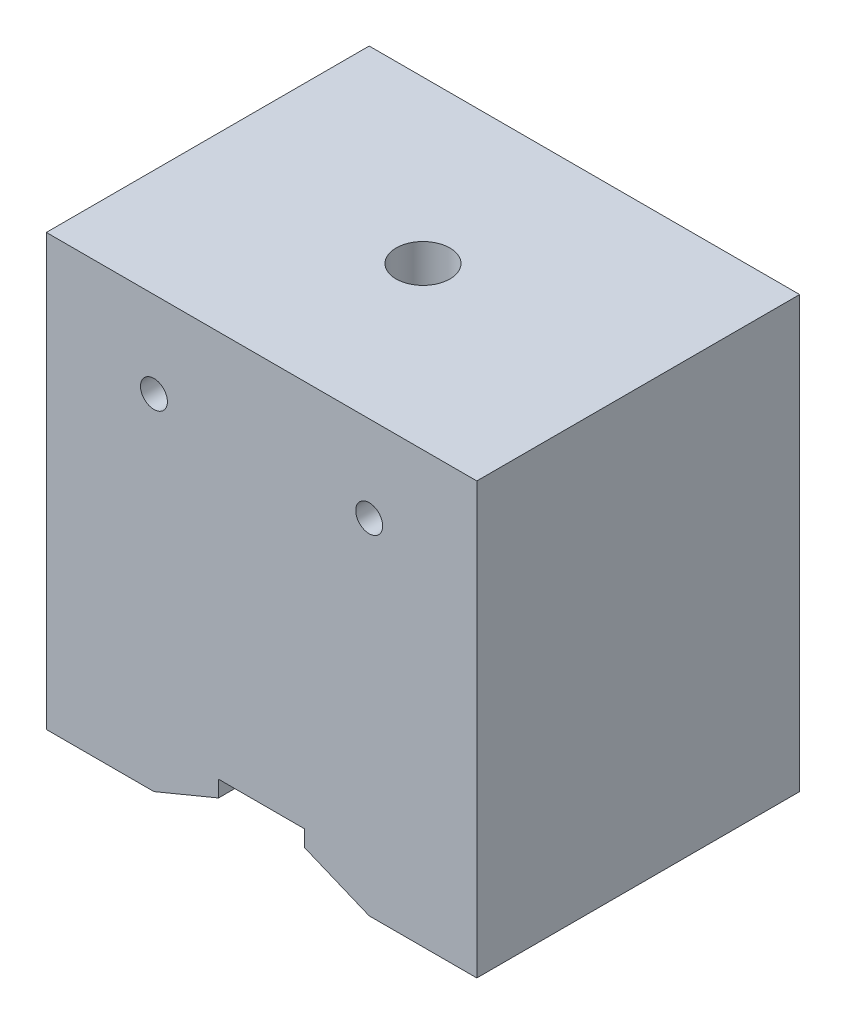
SolidWorks part; units mm, degrees
ref_plane "前视基准面" through (0, 0, 0) normal (0, 0, 1) x (1, 0, 0)
ref_plane "上视基准面" through (0, 0, 0) normal (0, 1, 0) x (1, 0, 0)
ref_plane "右视基准面" through (0, 0, 0) normal (1, 0, 0) x (0, 0, -1)
sketch "草图1" plane through (0, 0, 0) normal (0, 0, 1) x (1, 0, 0)
  line L1 (0, 0) -> (40, 0)
  line L2 (0, 0) -> (0, 40)
  line L3 (0, 40) -> (40, 40)
  line L4 (40, 0) -> (40, 40)
  dimension "D1" = 40
  dimension "D2" = 40
extrude "凸台-拉伸1" add sketch "草图1" along normal blind 30
sketch "草图2" plane through (0, 0, 30) normal (0, 0, 1) x (1, 0, 0)
  line L0 (10, 0) -> (16, 2.4853)
  line L1 (0, 0) -> (40, 0) construction
  line L2 (16, 2.4853) -> (16, 4)
  line L3 (16, 4) -> (24, 4)
  line L4 (24, 4) -> (24, 2.4853)
  line L7 (24, 2.4853) -> (30, 0)
  line L8 (30, 0) -> (10, 0)
  line L10 (20, 40) -> (20, -4.8116) construction
  line L11 (40, 40) -> (0, 40) construction
  dimension "D1" = 20
  dimension "D2" = 8
  dimension "D3" = 135
  dimension "D4" = 4
extrude "切除-拉伸1" cut sketch "草图2" against normal through all
hole_wizard "M6 螺纹孔1" positions "草图4" profile "草图3" tap size "M6" standard "Iso"
sketch "草图4" plane through (0, 40, 0) normal (0, 1, 0) x (1, 0, 0)
  line L0 (20, 0) -> (20, -23.4855) construction
  line L1 (40, 0) -> (0, 0) construction
  line L4 (0, -15) -> (27.0114, -15) construction
  line L5 (0, -30) -> (0, 0) construction
  point P0 (20, -15)
sketch "草图3" plane through (20, 40, 15) normal (1, 0, 0) x (0, 0, 1)
  line L0 (0, 0) -> (0, 16.5022)
  line L1 (0, 16.5022) -> (2.5, 15)
  line L2 (2.5, 15) -> (2.5, 0)
  line L5 (2.5, 0) -> (0, 0)
  line L10 (0, 16.5022) -> (-2.5, 15) construction
  line L11 (0, -6.35) -> (0, 107.95) construction
  dimension "螺纹孔钻头直径" = 5
  dimension "螺纹孔钻头深度" = 15
  dimension "导头角度" = 118
cosmetic thread "孔螺蚊线1" parameters "D1"=12, "D2"=6
hole_wizard "M3 螺纹孔1" positions "草图7" profile "草图5" tap size "M3" standard "Iso"
sketch "草图7" plane through (0, 0, 30) normal (0, 0, 1) x (1, 0, 0)
  line L0 (20, 40) -> (20, 6.7666) construction
  line L1 (40, 40) -> (0, 40) construction
  point P0 (10, 32)
  point P2 (30, 32)
  dimension "D1" = 20
  dimension "D2" = 8
sketch "草图5" plane through (10, 32, 30) normal (1, 0, 0) x (0, -1, 0)
  line L0 (0, 0) -> (0, 8.2511)
  line L1 (0, 8.2511) -> (1.25, 7.5)
  line L2 (1.25, 7.5) -> (1.25, 0)
  line L5 (1.25, 0) -> (0, 0)
  line L10 (0, 8.2511) -> (-1.25, 7.5) construction
  line L11 (0, -6.35) -> (0, 107.95) construction
  dimension "螺纹孔钻头直径" = 2.5
  dimension "螺纹孔钻头深度" = 7.5
  dimension "导头角度" = 118
cosmetic thread "孔螺蚊线2" parameters "D1"=6, "D2"=3
cosmetic thread "孔螺蚊线3" parameters "D1"=6, "D2"=3
